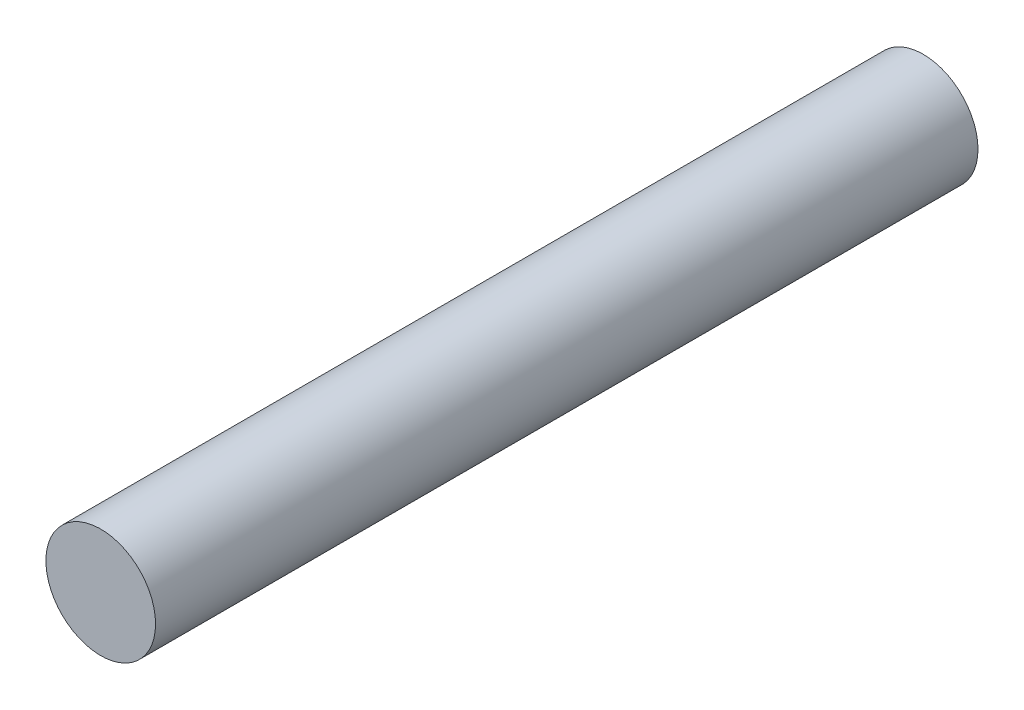
SolidWorks part; units mm, degrees
ref_plane "Front Plane" through (0, 0, 0) normal (0, 0, 1) x (1, 0, 0)
ref_plane "Top Plane" through (0, 0, 0) normal (0, 1, 0) x (1, 0, 0)
ref_plane "Right Plane" through (0, 0, 0) normal (1, 0, 0) x (0, 0, -1)
sketch "Sketch1" plane through (0, 0, 0) normal (0, 0, 1) x (1, 0, 0)
  circle A0 centre (0, 0) radius 4
  dimension "D1" = 8
extrude "Boss-Extrude1" add sketch "Sketch1" along normal blind 60
sketch "Sketch2" plane through (0, 0, 0) normal (0, 1, 0) x (1, 0, 0)
  line L0 (0, 0) -> (0, -60) construction
  line L1 (-4, -60) -> (4, -60) construction
  line L2 (4, -60) -> (4, 0) construction
  line L3 (-4, -33) -> (4, -33)
  line L4 (-4, -33) -> (-4, -27)
  line L5 (-4, -27) -> (4, -27)
  line L6 (4, -33) -> (4, -27)
  line L7 (-4, -33) -> (4, -27) construction
  line L8 (-4, -27) -> (4, -33) construction
  point P5 (0, -30)
  dimension "D1" = 6
extrude "Cut-Extrude1" cut sketch "Sketch2" against normal blind 1 from offset 3 offset against normal yes
